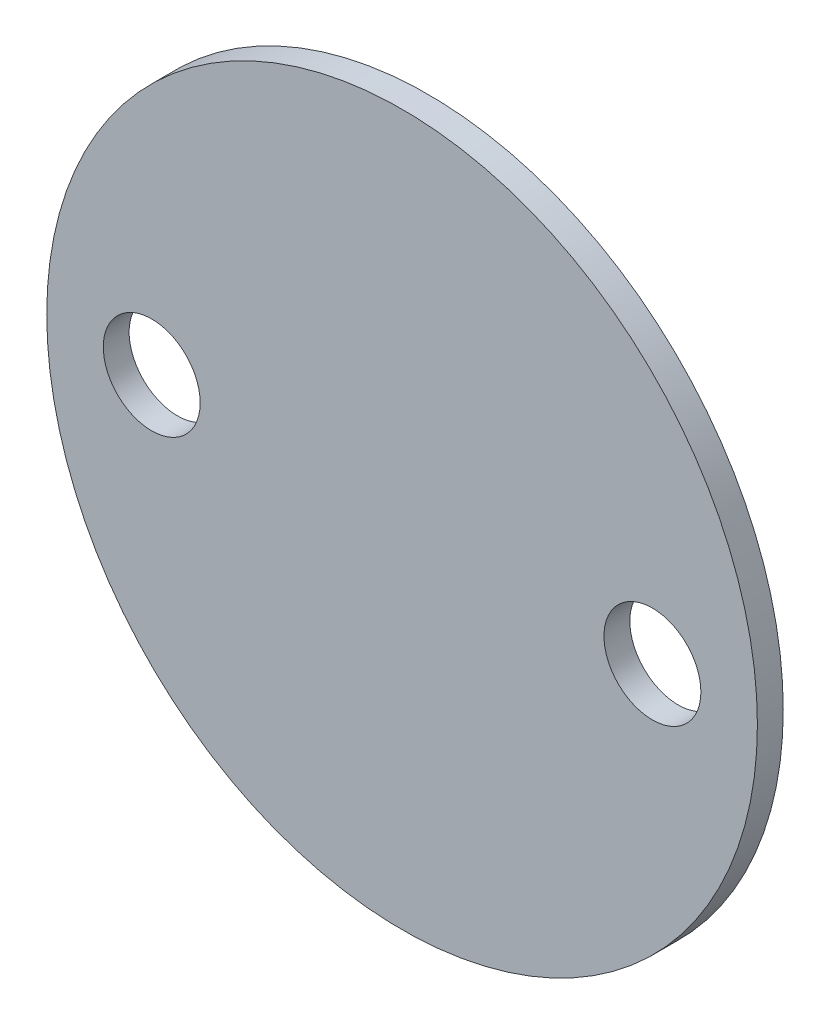
SolidWorks part; units mm, degrees
ref_plane "Plan de face" through (0, 0, 0) normal (0, 0, 1) x (1, 0, 0)
ref_plane "Plan de dessus" through (0, 0, 0) normal (0, 1, 0) x (1, 0, 0)
ref_plane "Plan de droite" through (0, 0, 0) normal (1, 0, 0) x (0, 0, -1)
sketch "Esquisse1" plane through (0, 0, 0) normal (0, 0, 1) x (1, 0, 0)
  line L0 (-18.8535, 0) -> (3.1465, 0) construction
  line L1 (-7.8535, 11) -> (-7.8535, -11) construction
  circle A0 centre (-7.8535, 0) radius 11
  circle A1 centre (-15.6035, 0) radius 1.5
  circle A2 centre (-0.1035, 0) radius 1.5
  point P12 (-72.5684, 27.5218)
  dimension "D1" = 7.75
  dimension "D2" = 22
  dimension "D3" = 7.75
extrude "Boss.-Extru.1" add sketch "Esquisse1" along normal blind 0.8
